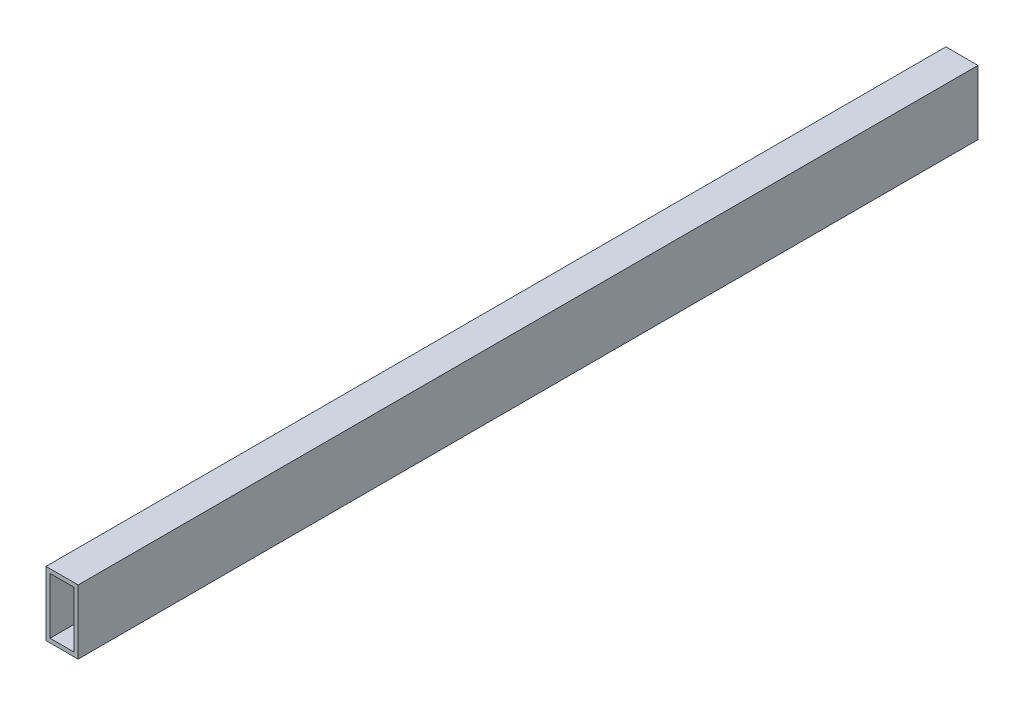
SolidWorks part; units mm, degrees
material "6061-T6 (SS)"
ref_plane "Front Plane" through (0, 0, 0) normal (0, 0, 1) x (1, 0, 0)
ref_plane "Top Plane" through (0, 0, 0) normal (0, 1, 0) x (1, 0, 0)
ref_plane "Right Plane" through (0, 0, 0) normal (1, 0, 0) x (0, 0, -1)
sketch "Sketch1" plane through (0, 0, 0) normal (0, 0, 1) x (1, 0, 0)
  line L1 (-12.7, 25.4) -> (12.7, 25.4)
  line L2 (-12.7, 25.4) -> (-12.7, -25.4)
  line L3 (-12.7, -25.4) -> (12.7, -25.4)
  line L4 (12.7, 25.4) -> (12.7, -25.4)
  line L5 (-12.7, 25.4) -> (12.7, -25.4) construction
  line L6 (-12.7, -25.4) -> (12.7, 25.4) construction
  line L7 (-9.4996, 22.1996) -> (9.4996, 22.1996)
  line L8 (-9.4996, 22.1996) -> (-9.4996, -22.1996)
  line L9 (-9.4996, -22.1996) -> (9.4996, -22.1996)
  line L10 (9.4996, 22.1996) -> (9.4996, -22.1996)
  line L11 (-9.4996, 22.1996) -> (9.4996, -22.1996) construction
  line L12 (-9.4996, -22.1996) -> (9.4996, 22.1996) construction
  point P0 (0, 0)
  point P6 (0, 0)
  dimension "D1" = 3.2004
  dimension "D2" = 25.4
  dimension "D3" = 50.8
  dimension "D4" = 3.2004
extrude "Boss-Extrude1" add sketch "Sketch1" along normal mid plane 1498.6 contours L2 L1 L4 L3
sketch "Sketch2" plane through (0, 0, 749.3) normal (0, 0, 1) x (1, 0, 0)
  line L1 (-12.7, 25.4) -> (12.7, 25.4)
  line L2 (-12.7, 25.4) -> (-12.7, -25.4)
  line L3 (-12.7, -25.4) -> (12.7, -25.4)
  line L4 (12.7, 25.4) -> (12.7, -25.4)
extrude "Cut-Extrude1" cut sketch "Sketch2" against normal blind 393.7
sketch "Sketch3" plane through (0, 0, -749.3) normal (0, 0, -1) x (-1, 0, 0)
  line L1 (-12.7, 25.4) -> (12.7, 25.4)
  line L2 (-12.7, 25.4) -> (-12.7, -25.4)
  line L3 (-12.7, -25.4) -> (12.7, -25.4)
  line L4 (12.7, 25.4) -> (12.7, -25.4)
extrude "Cut-Extrude2" cut sketch "Sketch3" against normal blind 393.7
equation "\"D1@Cut-Extrude1\"=(59 - (\"chassis-length\" - 2)) / 2"
equation "\"D1@Cut-Extrude2\"=(59 - (\"chassis-length\" - 2)) / 2"
equation "\"chassis-length\" = 30"
equation "\"chassis-width\" = 30"
